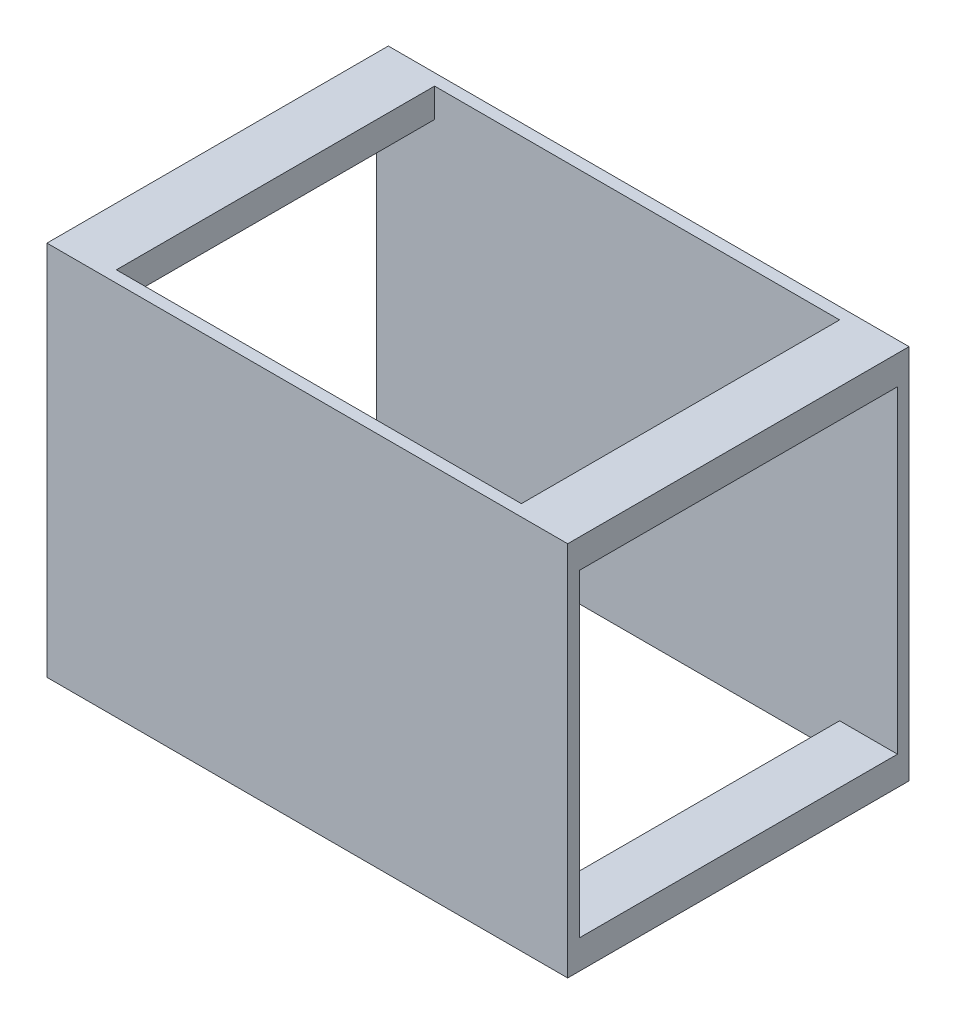
SolidWorks part; units mm, degrees
ref_plane "Front Plane" through (0, 0, 0) normal (0, 0, 1) x (1, 0, 0)
ref_plane "Top Plane" through (0, 0, 0) normal (0, 1, 0) x (1, 0, 0)
ref_plane "Right Plane" through (0, 0, 0) normal (1, 0, 0) x (0, 0, -1)
sketch "Sketch1" plane through (0, 0, 0) normal (0, 0, 1) x (1, 0, 0)
  line L1 (-45, 32.5) -> (45, 32.5)
  line L2 (-45, 32.5) -> (-45, -32.5)
  line L3 (-45, -32.5) -> (45, -32.5)
  line L4 (45, 32.5) -> (45, -32.5)
  line L5 (-45, 32.5) -> (45, -32.5) construction
  line L6 (-45, -32.5) -> (45, 32.5) construction
  point P0 (0, 0)
  dimension "D1" = 90
  dimension "D2" = 65
extrude "Boss-Extrude1" add sketch "Sketch1" along normal blind 2
sketch "Sketch2" plane through (0, 0, 2) normal (0, 0, 1) x (1, 0, 0)
  line L1 (-45, 32.5) -> (-35, 32.5)
  line L2 (-45, 32.5) -> (-45, 27.5)
  line L3 (-45, 27.5) -> (-35, 27.5)
  line L4 (-35, 32.5) -> (-35, 27.5)
  dimension "D1" = 10
  dimension "D2" = 5
extrude "Boss-Extrude2" add sketch "Sketch2" along normal blind 55
mirror "Mirror1" about plane through (0, 0, 0) normal (1, 0, 0) of "Boss-Extrude2" second plane through (0, 0, 0) second plane normal (0, 1, 0)
sketch "Sketch3" plane through (0, 0, 57) normal (0, 0, 1) x (1, 0, 0)
  line L0 (45, -32.5) -> (45, -27.5) construction
  line L1 (-45, 32.5) -> (45, 32.5)
  line L2 (-45, 32.5) -> (-45, -32.5)
  line L3 (-45, -32.5) -> (45, -32.5)
  line L4 (45, 32.5) -> (45, -32.5)
  line L5 (-45, 32.5) -> (45, -32.5) construction
  line L6 (-45, -32.5) -> (45, 32.5) construction
  line L7 (35, -32.5) -> (45, -32.5) construction
  point P0 (0, 0)
extrude "Boss-Extrude3" add sketch "Sketch3" along normal blind 2
